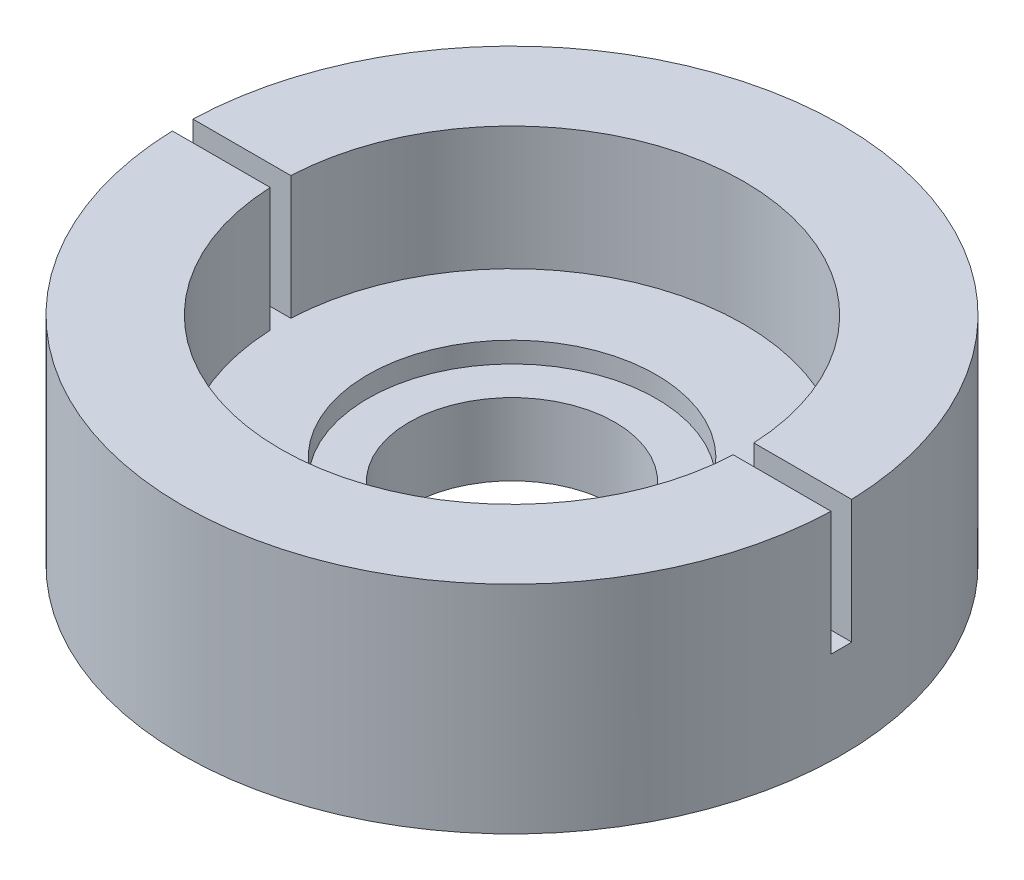
SolidWorks part; units mm, degrees
ref_plane "Front Plane" through (0, 0, 0) normal (0, 0, 1) x (1, 0, 0)
ref_plane "Top Plane" through (0, 0, 0) normal (0, 1, 0) x (1, 0, 0)
ref_plane "Right Plane" through (0, 0, 0) normal (1, 0, 0) x (0, 0, -1)
sketch "Sketch1" plane through (0, 0, 0) normal (0, 1, 0) x (1, 0, 0)
  line L0 (0, 0) -> (0, 12.5) construction
  circle A0 centre (0, 0) radius 16
  circle A1 centre (0, 0) radius 5
  circle A2 centre (0, 12.5) radius 1.975
  circle A3 centre (12.5, 0) radius 1.975
  circle A4 centre (0, -12.5) radius 1.975
  circle A5 centre (-12.5, 0) radius 1.975
  point P6 (-21.5177, -11.1537)
  point P8 (0, 0)
  point P9 (0, 0)
  point P15 (0, 0)
  dimension "D1" = 32
  dimension "D2" = 10
  dimension "D4" = 3.95
  dimension "D3" = 12.5
  dimension "D5" = 4
extrude "Boss-Extrude1" add sketch "Sketch1" along normal blind 3.5
sketch "Sketch2" plane through (0, 3.5, 0) normal (0, 1, 0) x (1, 0, 0)
  circle A0 centre (0, 0) radius 16
extrude "Boss-Extrude2" add sketch "Sketch2" along normal blind 1
sketch "Sketch3" plane through (0, 4.5, 0) normal (0, 1, 0) x (1, 0, 0)
  circle A0 centre (0, 0) radius 11.25
  circle A1 centre (0, 0) radius 16 construction
  circle A2 centre (0, 0) radius 16
  dimension "D1" = 22.5
extrude "Boss-Extrude3" add sketch "Sketch3" along normal blind 6
sketch "Sketch4" plane through (0, 10.5, 0) normal (0, 1, 0) x (1, 0, 0)
  line L1 (-16, -0.5) -> (16, -0.5)
  line L2 (-16, -0.5) -> (-16, 0.5)
  line L3 (-16, 0.5) -> (16, 0.5)
  line L4 (16, -0.5) -> (16, 0.5)
  line L5 (-16, -0.5) -> (16, 0.5) construction
  line L6 (-16, 0.5) -> (16, -0.5) construction
  circle A0 centre (0, 0) radius 16 construction
  point P0 (0, 0)
  dimension "D1" = 1
extrude "Cut-Extrude1" cut sketch "Sketch4" against normal up to surface (6 mm away) up to face at (0, 4.5, 11.25)
sketch "Sketch5" plane through (0, 4.5, 0) normal (0, 1, 0) x (1, 0, 0)
  circle A0 centre (0, 0) radius 7
  dimension "D1" = 14
extrude "Cut-Extrude2" cut sketch "Sketch5" against normal blind 1
